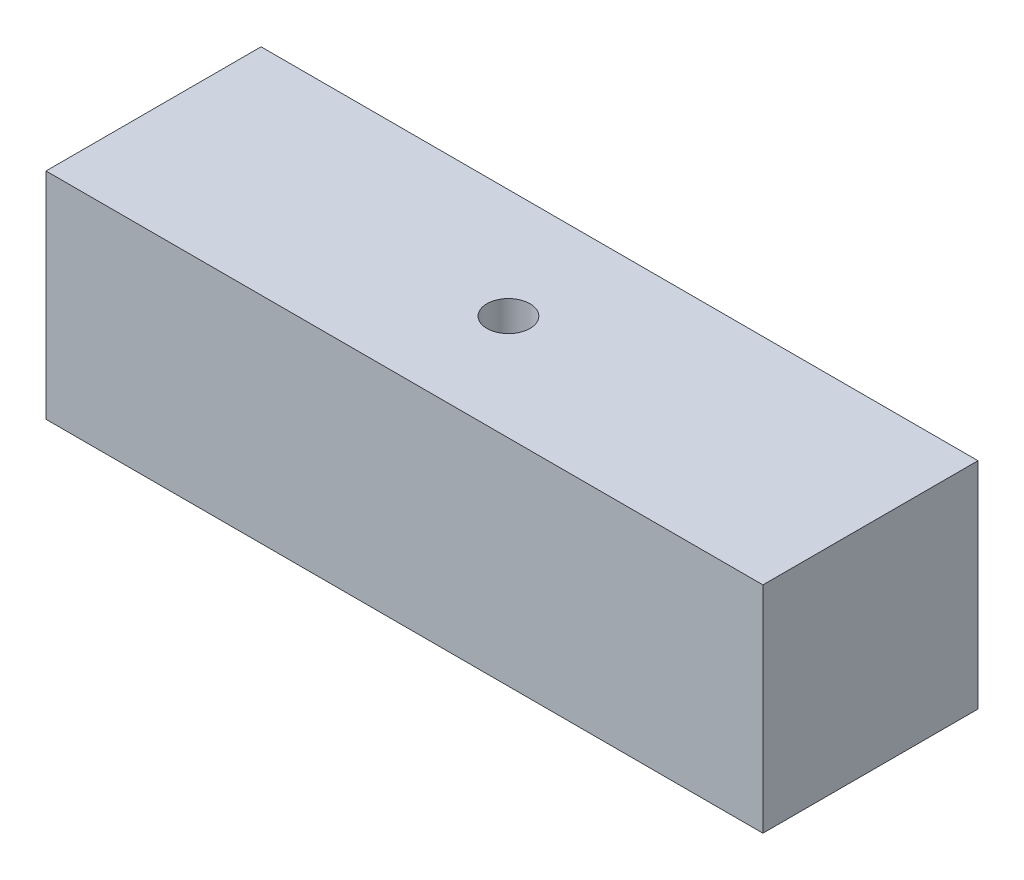
SolidWorks part; units mm, degrees
ref_plane "Plan de face" through (0, 0, 0) normal (0, 0, 1) x (1, 0, 0)
ref_plane "Plan de dessus" through (0, 0, 0) normal (0, 1, 0) x (1, 0, 0)
ref_plane "Plan de droite" through (0, 0, 0) normal (1, 0, 0) x (0, 0, -1)
sketch "Esquisse1" plane through (0, 0, 0) normal (0, 1, 0) x (1, 0, 0)
  line L1 (-38.9206, 23.3028) -> (11.0794, 23.3028)
  line L2 (-38.9206, 23.3028) -> (-38.9206, 8.3028)
  line L3 (-38.9206, 8.3028) -> (11.0794, 8.3028)
  line L4 (11.0794, 23.3028) -> (11.0794, 8.3028)
  dimension "D1" = 50
  dimension "D2" = 15
extrude "Boss.-Extru.1" add sketch "Esquisse1" along normal blind 15
sketch "Esquisse2" plane through (0, 15, 0) normal (0, 1, 0) x (1, 0, 0)
  circle A0 centre (-14.0287, 15.6638) radius 1.5
  point P0 (-14.0287, 15.6638)
  point P4 (-13.9206, 15.8028)
  dimension "D1" = 3
extrude "Enlèv. mat.-Extru.1" cut sketch "Esquisse2" against normal blind 5.5
